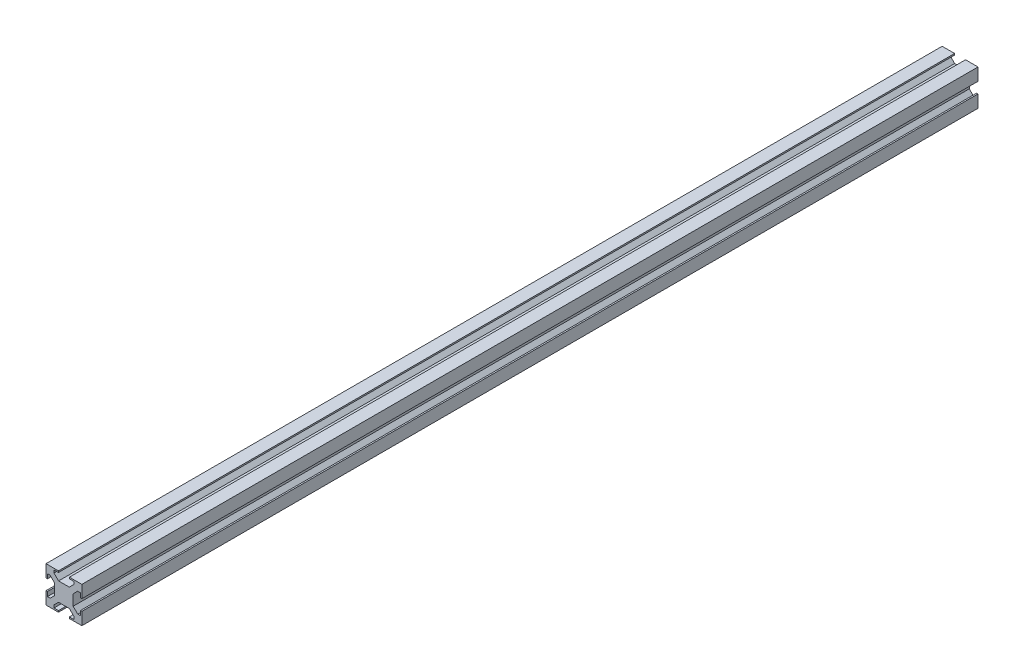
SolidWorks part; units mm, degrees
ref_plane "前视基准面" through (0, 0, 0) normal (0, 0, 1) x (1, 0, 0)
ref_plane "上视基准面" through (0, 0, 0) normal (0, 1, 0) x (1, 0, 0)
ref_plane "右视基准面" through (0, 0, 0) normal (1, 0, 0) x (0, 0, -1)
sketch "草图1" plane through (0, 0, 0) normal (0, 0, 1) x (1, 0, 0)
  line L0 (30, 10) -> (10, -10) construction
  line L1 (-10, -10) -> (30, -10)
  line L2 (-10, -10) -> (-10, 10)
  line L3 (-10, 10) -> (30, 10)
  line L4 (10, -10) -> (10, 10)
  line L5 (-10, -10) -> (10, 10) construction
  line L6 (-10, 10) -> (10, -10) construction
  line L7 (30, -10) -> (10, 10) construction
  line L8 (30, -10) -> (30, 10)
  line L9 (-3.05, 10) -> (-3.05, 9.2)
  line L10 (-3.05, 9.2) -> (-5.55, 9.2)
  line L11 (-5.55, 9.2) -> (-5.55, 7.7)
  line L12 (-5.55, 7.7) -> (-3, 5.15)
  line L13 (-3, 5.15) -> (3, 5.15)
  line L14 (0, -1000) -> (0, 49000) construction
  line L15 (-1000, 0) -> (49000, 0) construction
  line L16 (5.55, 7.7) -> (3, 5.15)
  line L17 (5.55, 9.2) -> (5.55, 7.7)
  line L18 (3.05, 9.2) -> (5.55, 9.2)
  line L19 (3.05, 10) -> (3.05, 9.2)
  line L20 (10, 3.05) -> (9.2, 3.05)
  line L21 (9.2, 3.05) -> (9.2, 5.55)
  line L22 (9.2, 5.55) -> (7.7, 5.55)
  line L23 (7.7, 5.55) -> (5.15, 3)
  line L24 (5.15, 3) -> (5.15, -3)
  line L25 (7.7, -5.55) -> (5.15, -3)
  line L26 (9.2, -5.55) -> (7.7, -5.55)
  line L27 (9.2, -3.05) -> (9.2, -5.55)
  line L28 (10, -3.05) -> (9.2, -3.05)
  line L29 (3.05, -10) -> (3.05, -9.2)
  line L30 (3.05, -9.2) -> (5.55, -9.2)
  line L31 (5.55, -9.2) -> (5.55, -7.7)
  line L32 (5.55, -7.7) -> (3, -5.15)
  line L33 (3, -5.15) -> (-3, -5.15)
  line L34 (-5.55, -7.7) -> (-3, -5.15)
  line L35 (-5.55, -9.2) -> (-5.55, -7.7)
  line L36 (-3.05, -9.2) -> (-5.55, -9.2)
  line L37 (-3.05, -10) -> (-3.05, -9.2)
  line L38 (-10, -3.05) -> (-9.2, -3.05)
  line L39 (-9.2, -3.05) -> (-9.2, -5.55)
  line L40 (-9.2, -5.55) -> (-7.7, -5.55)
  line L41 (-7.7, -5.55) -> (-5.15, -3)
  line L42 (-5.15, -3) -> (-5.15, 3)
  line L43 (-7.7, 5.55) -> (-5.15, 3)
  line L44 (-9.2, 5.55) -> (-7.7, 5.55)
  line L45 (-9.2, 3.05) -> (-9.2, 5.55)
  line L46 (-10, 3.05) -> (-9.2, 3.05)
  line L47 (30, 3.05) -> (29.2, 3.05)
  line L48 (29.2, 3.05) -> (29.2, 5.55)
  line L49 (29.2, 5.55) -> (27.7, 5.55)
  line L50 (27.7, 5.55) -> (25.15, 3)
  line L51 (25.15, -3) -> (25.15, 3)
  line L52 (27.7, -5.55) -> (25.15, -3)
  line L53 (29.2, -5.55) -> (27.7, -5.55)
  line L54 (29.2, -3.05) -> (29.2, -5.55)
  line L55 (30, -3.05) -> (29.2, -3.05)
  point P0 (0, 0)
  point P8 (20, 0)
  point P20 (0, 5.15)
  point P24 (25.15, 0)
  point P34 (5.15, 0)
  point P45 (0, -5.15)
  point P56 (-5.15, 0)
  point P60 (0, 0)
  dimension "D1" = 20
  dimension "D2" = 20
  dimension "D3" = 6
  dimension "D4" = 3.05
  dimension "D5" = 0.8
  dimension "D6" = 1.5
  dimension "D7" = 2.5
  dimension "D8" = 4
extrude "凸台-拉伸1" add sketch "草图1" along normal blind 500
